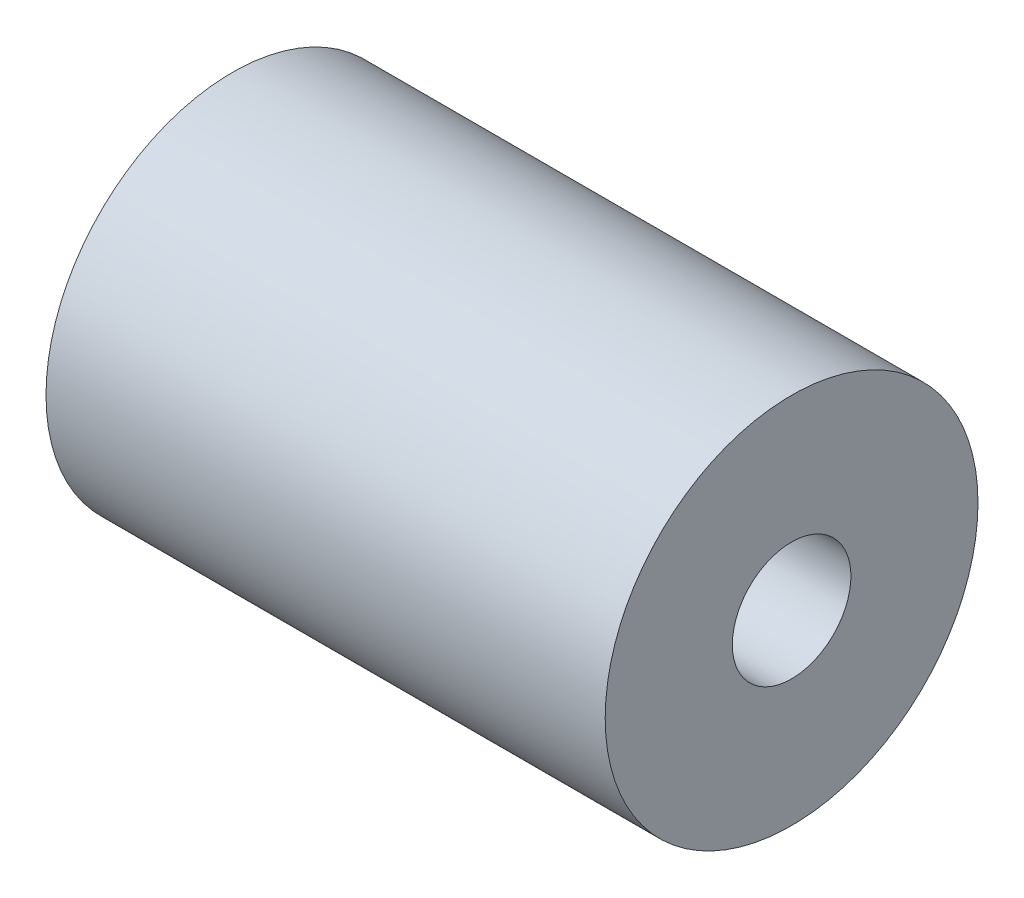
SolidWorks part; units mm, degrees
material "6061 Alloy"
ref_plane "Front Plane" through (0, 0, 0) normal (0, 0, 1) x (1, 0, 0)
ref_plane "Top Plane" through (0, 0, 0) normal (0, 1, 0) x (1, 0, 0)
ref_plane "Right Plane" through (0, 0, 0) normal (1, 0, 0) x (0, 0, -1)
sketch "Sketch1" plane through (0, 0, 0) normal (1, 0, 0) x (0, 0, -1)
  circle A0 centre (0, 0) radius 2.0193
  circle A1 centre (0, 0) radius 6.35
  dimension "D1" = 12.7
  dimension "D2" = 4.0386
extrude "Boss-Extrude1" add sketch "Sketch1" along normal blind 19.05
